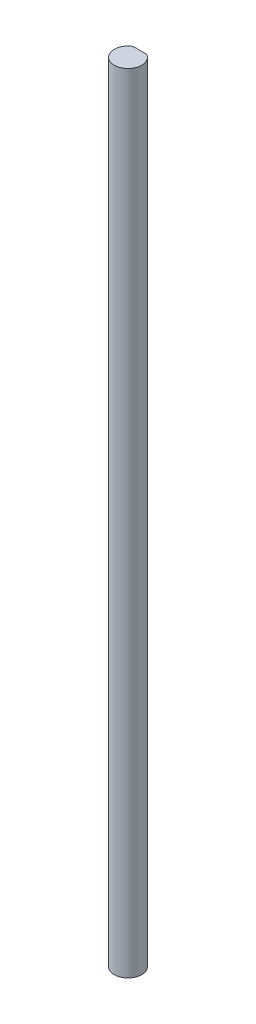
SolidWorks part; units mm, degrees
material "AISI 1045 Steel, cold drawn"
ref_plane "Front Plane" through (0, 0, 0) normal (0, 0, 1) x (1, 0, 0)
ref_plane "Top Plane" through (0, 0, 0) normal (0, 1, 0) x (1, 0, 0)
ref_plane "Right Plane" through (0, 0, 0) normal (1, 0, 0) x (0, 0, -1)
sketch "Sketch1" plane through (0, 0, 0) normal (0, 1, 0) x (1, 0, 0)
  line L0 (-1.5875, 2.7496) -> (1.5875, 2.7496)
  arc A0 (-1.5875, 2.7496) -> (1.5875, 2.7496) centre (0, 0) ccw
  dimension "D1" = 6.35
  dimension "D2" = 3.175
extrude "Boss-Extrude1" add sketch "Sketch1" along normal blind 181.5
